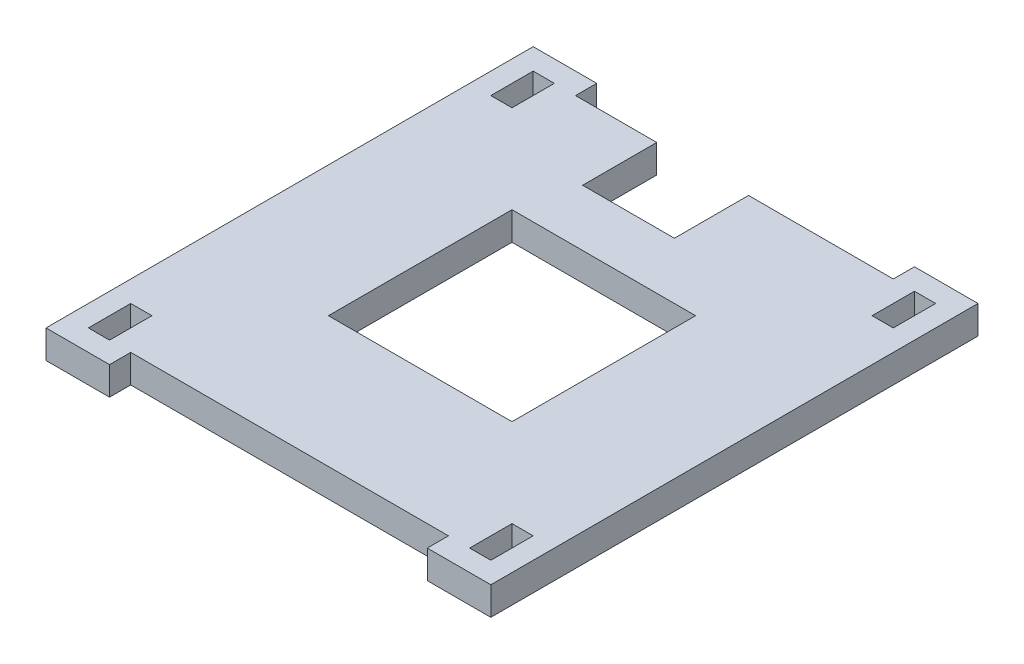
SolidWorks part; units mm, degrees
ref_plane "Front Plane" through (0, 0, 0) normal (0, 0, 1) x (1, 0, 0)
ref_plane "Top Plane" through (0, 0, 0) normal (0, 1, 0) x (1, 0, 0)
ref_plane "Right Plane" through (0, 0, 0) normal (1, 0, 0) x (0, 0, -1)
sketch "Sketch1" plane through (0, 0, 0) normal (0, 1, 0) x (1, 0, 0)
  line L1 (0, 0) -> (63, 0)
  line L2 (0, 0) -> (0, 63)
  line L3 (0, 63) -> (63, 63)
  line L4 (63, 0) -> (63, 63)
  dimension "D1" = 63
  dimension "D2" = 63
extrude "Boss-Extrude1" add sketch "Sketch1" along normal blind 4
sketch "Sketch2" plane through (0, 4, 0) normal (0, 1, 0) x (1, 0, 0)
  line L0 (0, 0) -> (63, 0) construction
  line L1 (3, 0) -> (6, 0)
  line L2 (3, 0) -> (3, 6)
  line L3 (3, 6) -> (6, 6)
  line L4 (6, 0) -> (6, 6)
  line L5 (63, 63) -> (0, 63) construction
  line L6 (57, 0) -> (60, 0)
  line L7 (57, 0) -> (57, 6)
  line L8 (57, 6) -> (60, 6)
  line L9 (60, 0) -> (60, 6)
  line L10 (57, 63) -> (60, 63)
  line L11 (57, 63) -> (57, 57)
  line L12 (57, 57) -> (60, 57)
  line L13 (60, 63) -> (60, 57)
  line L15 (3, 63) -> (6, 63)
  line L16 (3, 63) -> (3, 57)
  line L17 (3, 57) -> (6, 57)
  line L18 (6, 63) -> (6, 57)
  line L19 (0, 63) -> (0, 0) construction
  line L20 (63, 0) -> (63, 63) construction
  dimension "D1" = 3
  dimension "D2" = 3
  dimension "D3" = 6
  dimension "D4" = 3
extrude "Cut-Extrude1" cut sketch "Sketch2" against normal up to surface (4 mm away) up to face at (31.5, 0, -31.5)
sketch "Sketch3" plane through (0, 0, 0) normal (0, 0, 1) x (1, 0, 0)
  line L0 (6, 4) -> (57, 4) construction
  line L1 (0, 4) -> (9, 4)
  line L2 (0, 4) -> (0, 0)
  line L3 (0, 0) -> (9, 0)
  line L4 (9, 4) -> (9, 0)
  line L5 (6, 0) -> (57, 0) construction
  line L7 (63, 4) -> (54, 4)
  line L8 (63, 4) -> (63, 0)
  line L9 (63, 0) -> (54, 0)
  line L10 (54, 4) -> (54, 0)
  dimension "D1" = 9
  dimension "D2" = 9
extrude "Boss-Extrude2" add sketch "Sketch3" along normal blind 3
sketch "Sketch4" plane through (0, 0, -63) normal (0, 0, -1) x (-1, 0, 0)
  line L0 (-57, 4) -> (-6, 4) construction
  line L2 (0, 4) -> (-9, 4)
  line L3 (0, 4) -> (0, 0)
  line L4 (0, 0) -> (-9, 0)
  line L5 (-57, 0) -> (-6, 0) construction
  line L6 (-54, 4) -> (-63, 4)
  line L7 (-54, 4) -> (-54, 0)
  line L8 (-54, 0) -> (-63, 0)
  line L9 (-63, 4) -> (-63, 0)
  line L10 (-9, 4) -> (-9, 0)
  dimension "D1" = 9
  dimension "D2" = 9
extrude "Boss-Extrude3" add sketch "Sketch4" along normal blind 3
sketch "Sketch5" plane through (0, 4, 0) normal (0, 1, 0) x (1, 0, 0)
  line L0 (0, 66) -> (0, -3) construction
  line L1 (18.5, 18.5) -> (44.5, 18.5)
  line L2 (18.5, 18.5) -> (18.5, 44.5)
  line L3 (18.5, 44.5) -> (44.5, 44.5)
  line L4 (44.5, 18.5) -> (44.5, 44.5)
  line L11 (9, 0) -> (54, 0) construction
  dimension "D1" = 26
  dimension "D2" = 26
  dimension "D3" = 18.5
  dimension "D4" = 18.5
extrude "Cut-Extrude2" cut sketch "Sketch5" against normal up to surface (4 mm away) up to face at (58.5, 0, -60)
sketch "Sketch6" plane through (0, 4, 0) normal (0, 1, 0) x (1, 0, 0)
  line L1 (33.5, 63) -> (20.5, 63)
  line L2 (33.5, 63) -> (33.5, 52.5)
  line L3 (33.5, 52.5) -> (20.5, 52.5)
  line L4 (20.5, 63) -> (20.5, 52.5)
  line L5 (0, 66) -> (0, -3) construction
  line L6 (44.5, 44.5) -> (18.5, 44.5) construction
  dimension "D1" = 13
  dimension "D2" = 20.5
  dimension "D3" = 8
extrude "Cut-Extrude3" cut sketch "Sketch6" against normal up to surface (4 mm away) up to face at (31.5, 0, -31.5)
sketch "Sketch8" plane through (0, 0, 0) normal (0, -1, 0) x (1, 0, 0)
  line L0 (9, 0) -> (54, 0) construction
  line L1 (44.2826, -13) -> (37.7826, -13)
  line L2 (44.2826, -13) -> (44.2826, -7)
  line L3 (44.2826, -7) -> (37.7826, -7)
  line L4 (37.7826, -13) -> (37.7826, -7)
  dimension "D1" = 7
  dimension "D2" = 6
  dimension "D3" = 6.5
extrude "Cut-Extrude4" cut sketch "Sketch8" against normal blind 1.5
